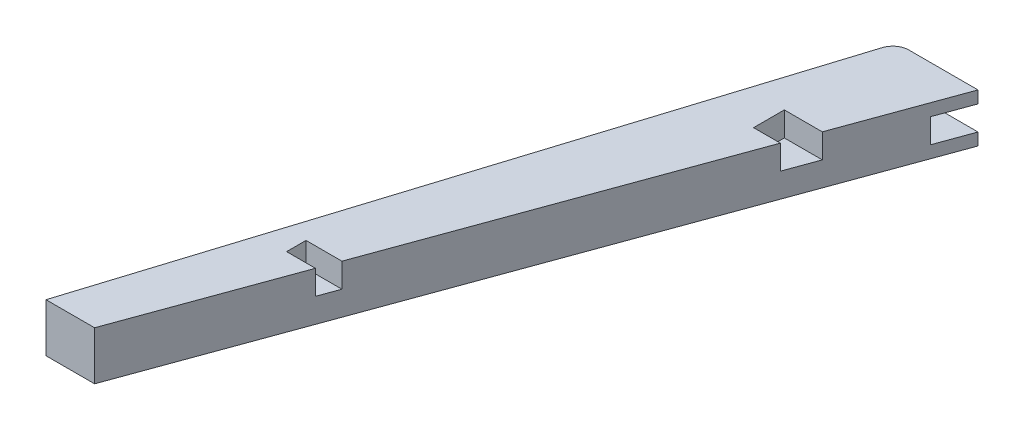
SolidWorks part; units mm, degrees
ref_plane "Alzado" through (0, 0, 0) normal (0, 0, 1) x (1, 0, 0)
ref_plane "Planta" through (0, 0, 0) normal (0, 1, 0) x (1, 0, 0)
ref_plane "Vista lateral" through (0, 0, 0) normal (1, 0, 0) x (0, 0, -1)
sketch "Croquis1" plane through (0, 0, 0) normal (0, 1, 0) x (1, 0, 0)
  line L8 (15, 0) -> (160.5881, 400)
  line L9 (160.5881, 400) -> (110.5881, 400)
  line L10 (110.5881, 400) -> (-15, 0)
  line L11 (-15, 0) -> (15, 0)
  point P2 (0, 0)
  point P6 (0, 0)
  dimension "D1" = 50
  dimension "D2" = 30
  dimension "D3" = 110
  dimension "D4" = 400
extrude "Saliente-Extruir1" add sketch "Croquis1" along normal mid plane 30
sketch "Croquis2" plane through (0, 0, -400) normal (0, 0, -1) x (-1, 0, 0)
  line L0 (-160.5881, 15) -> (-160.5881, -15) construction
  line L1 (-160.5881, 7.5) -> (-135.5881, 7.5)
  line L2 (-160.5881, 7.5) -> (-160.5881, -7.5)
  line L3 (-160.5881, -7.5) -> (-135.5881, -7.5)
  line L4 (-135.5881, 7.5) -> (-135.5881, -7.5)
  line L5 (-110.5881, 15) -> (-110.5881, -15) construction
  line L6 (-160.5881, 15) -> (-110.5881, 15) construction
  point P8 (-110.5881, 0)
  point P9 (-135.5881, 0)
  point P12 (-135.5881, 15)
  dimension "D1" = 15
extrude "Cortar-Extruir1" cut sketch "Croquis2" against normal blind 21.55
fillet "Redondeo2" radius 10 1 edges at (110.5881, 0, -400)
sketch "Croquis3" plane through (0, 15, 0) normal (0, 1, 0) x (1, 0, 0)
  line L0 (15, 0) -> (160.5881, 400) construction
  line L1 (111.4705, 329.5) -> (151.4705, 329.5)
  line L2 (111.4705, 329.5) -> (111.4705, 310.5)
  line L3 (111.4705, 310.5) -> (151.4705, 310.5)
  line L4 (151.4705, 329.5) -> (151.4705, 310.5)
  line L5 (111.4705, 329.5) -> (151.4705, 310.5) construction
  line L6 (111.4705, 310.5) -> (151.4705, 329.5) construction
  line L8 (33.5808, 112) -> (73.5808, 112)
  line L9 (33.5808, 112) -> (33.5808, 100)
  line L10 (33.5808, 100) -> (73.5808, 100)
  line L11 (73.5808, 112) -> (73.5808, 100)
  line L12 (33.5808, 112) -> (73.5808, 100) construction
  line L13 (33.5808, 100) -> (73.5808, 112) construction
  point P0 (131.4705, 320)
  point P7 (53.5808, 106)
  dimension "D1" = 19
  dimension "D2" = 20
  dimension "D3" = 12
  dimension "D4" = 20
  dimension "D5" = 80
  dimension "D6" = 100
extrude "Cortar-Extruir2" cut sketch "Croquis3" against normal blind 15
